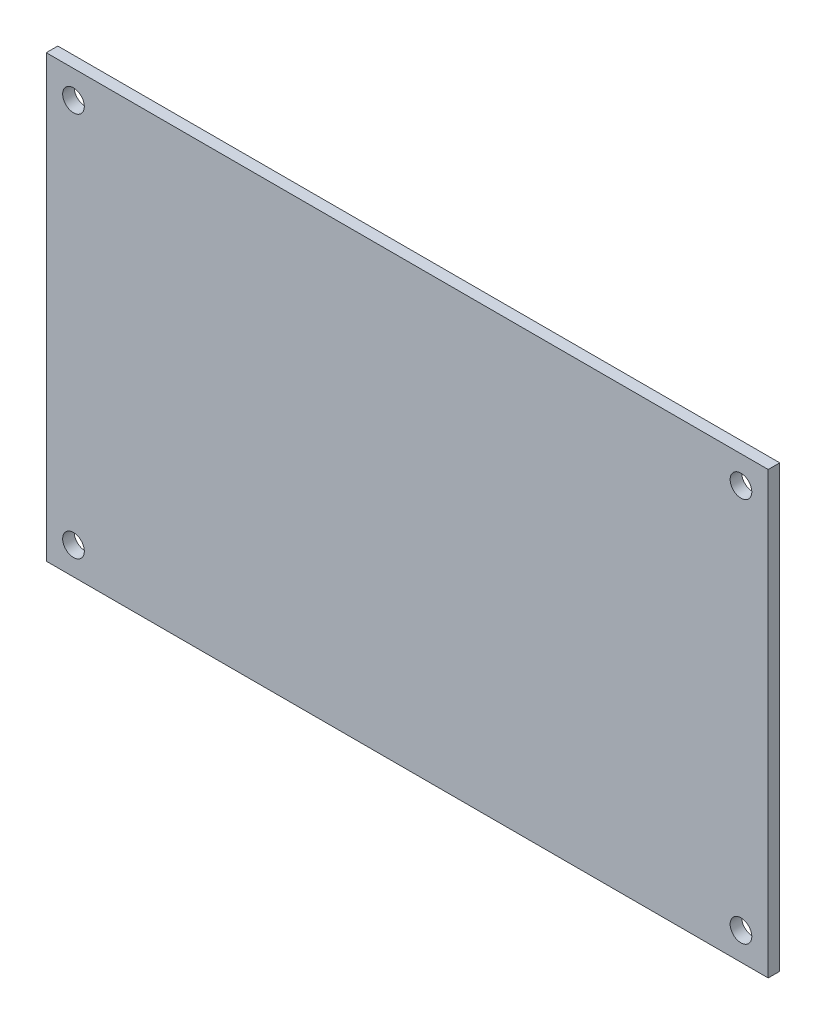
SolidWorks part; units mm, degrees
ref_plane "Front Plane" through (0, 0, 0) normal (0, 0, 1) x (1, 0, 0)
ref_plane "Top Plane" through (0, 0, 0) normal (0, 1, 0) x (1, 0, 0)
ref_plane "Right Plane" through (0, 0, 0) normal (1, 0, 0) x (0, 0, -1)
sketch "Sketch1" plane through (0, 0, 0) normal (0, 0, 1) x (1, 0, 0)
  line L0 (3.772, 3.83) -> (96.228, 3.83) construction
  line L1 (0, 0) -> (100, 0)
  line L2 (0, 0) -> (0, 61)
  line L3 (0, 61) -> (100, 61)
  line L4 (100, 0) -> (100, 61)
  line L5 (3.772, 57.17) -> (3.772, 3.83) construction
  line L7 (92, 65.4275) -> (80, 65.4275) construction
  line L8 (92, 65.4275) -> (92, 69.7425) construction
  line L9 (92, 69.7425) -> (80, 69.7425) construction
  line L10 (80, 65.4275) -> (80, 69.7425) construction
  line L11 (12.5, 65.4275) -> (6.9971, 65.4275) construction
  line L12 (12.5, 65.4275) -> (12.5, 74.3592) construction
  line L13 (12.5, 74.3592) -> (6.9971, 74.3592) construction
  line L14 (6.9971, 65.4275) -> (6.9971, 74.3592) construction
  circle A0 centre (3.772, 3.83) radius 1.5
  circle A1 centre (96.228, 3.83) radius 1.5
  circle A2 centre (3.772, 57.17) radius 1.5
  circle A3 centre (96.228, 57.17) radius 1.5
  point P13 (0, 30.5)
  point P14 (3.772, 30.5)
  point P15 (50, 3.83)
  point P16 (50, 0)
  dimension "D4" = 3
  dimension "D1" = 100
  dimension "D2" = 61
  dimension "D3" = 92.456
  dimension "D5" = 53.34
  dimension "D6" = 8
  dimension "D7" = 20
  dimension "D8" = 87.5
extrude "Boss-Extrude1" add sketch "Sketch1" along normal blind 1.6
